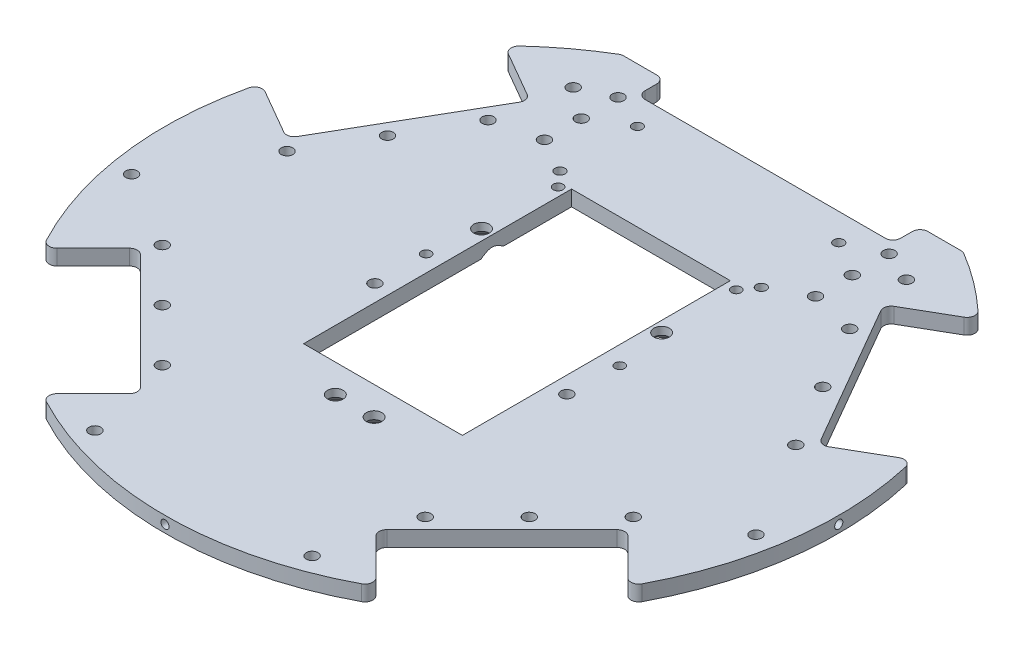
SolidWorks part; units mm, degrees
ref_plane "Front Plane" through (0, 0, 0) normal (0, 0, 1) x (1, 0, 0)
ref_plane "Top Plane" through (0, 0, 0) normal (0, 1, 0) x (1, 0, 0)
ref_plane "Right Plane" through (0, 0, 0) normal (1, 0, 0) x (0, 0, -1)
sketch "Sketch1" plane through (0, 0, 0) normal (0, 1, 0) x (1, 0, 0)
  line L0 (0, 75) -> (0, -70.0325) construction
  line L1 (0, 0) -> (57.1577, 33) construction
  line L2 (0, 0) -> (46.669, -46.669) construction
  line L3 (45.6577, 52.9186) -> (68.6577, 13.0814)
  line L4 (-44.0908, 75) -> (44.0908, 75) construction
  line L5 (62.9325, -30.4056) -> (30.4056, -62.9325)
  line L6 (45.6577, 52.9186) -> (61.1636, 61.8709)
  line L7 (68.6577, 13.0814) -> (84.1636, 22.0338)
  line L8 (30.4056, -62.9325) -> (43.0661, -75.593)
  line L9 (62.9325, -30.4056) -> (75.593, -43.0661)
  line L10 (-33, 69) -> (33, 69)
  line L11 (33, 69) -> (33, 75)
  line L12 (33, 75) -> (44.0908, 75)
  line L13 (0, 0) -> (-46.669, -46.669) construction
  line L14 (0, 0) -> (-57.1577, 33) construction
  line L15 (-33, 75) -> (-44.0908, 75)
  line L16 (-33, 69) -> (-33, 75)
  line L17 (-62.9325, -30.4056) -> (-75.593, -43.0661)
  line L18 (-30.4056, -62.9325) -> (-43.0661, -75.593)
  line L19 (-68.6577, 13.0814) -> (-84.1636, 22.0338)
  line L20 (-45.6577, 52.9186) -> (-61.1636, 61.8709)
  line L21 (-62.9325, -30.4056) -> (-30.4056, -62.9325)
  line L22 (-45.6577, 52.9186) -> (-68.6577, 13.0814)
  arc A0 (-43.0661, -75.593) -> (43.0661, -75.593) centre (0, 0) ccw
  arc A1 (61.1636, 61.8709) -> (44.0908, 75) centre (0, 0) ccw
  arc A2 (75.593, -43.0661) -> (84.1636, 22.0338) centre (0, 0) ccw
  arc A3 (-75.593, -43.0661) -> (-84.1636, 22.0338) centre (0, 0) cw
  arc A4 (-61.1636, 61.8709) -> (-44.0908, 75) centre (0, 0) cw
  point P27 (0, 69)
  dimension "D1" = 87
  dimension "D2" = 75
  dimension "D3" = 66
  dimension "D4" = 60
  dimension "D5" = 45
  dimension "D6" = 46
  dimension "D7" = 46
  dimension "D8" = 33
  dimension "D9" = 6
extrude "Boss-Extrude1" add sketch "Sketch1" along normal mid plane 4
fillet "Fillet1" radius 2 20 edges at (33, 0, -75) (-33, 0, -75) (44.0908, 0, -75) (68.6577, 0, -13.0814) (84.1636, 0, -22.0338) (45.6577, 0, -52.9186) (61.1636, 0, -61.8709) (62.9325, 0, 30.4056) (43.0661, 0, 75.593) (30.4056, 0, 62.9325) (75.593, 0, 43.0661) (-43.0661, 0, 75.593) (-30.4056, 0, 62.9325) (-75.593, 0, 43.0661) (-62.9325, 0, 30.4056) (-68.6577, 0, -13.0814) (-84.1636, 0, -22.0338) (-45.6577, 0, -52.9186) (-44.0908, 0, -75) (-61.1636, 0, -61.8709)
sketch "Sketch2" plane through (0, -2, 0) normal (0, -1, 0) x (-1, 0, 0)
  line L0 (46.6936, 43.1244) -> (65.6936, 10.2154) construction
  line L1 (60.8112, -26.8701) -> (33.9411, -53.7401) construction
  line L2 (46.6577, 51.1865) -> (67.6577, 14.8135) construction
  line L3 (61.5183, -31.8198) -> (31.8198, -61.5183) construction
  line L4 (70.3897, 14.0814) -> (81.8562, 20.7016) construction
  line L5 (73.7091, -41.1822) -> (64.3467, -31.8198) construction
  line L6 (35, 65) -> (35, 46) construction
  line L7 (26, 61) -> (26, 41) construction
  line L8 (35, 75) -> (43.5431, 75) construction
  line L9 (-33, 69) -> (33, 69) construction
  line L10 (-33, 69) -> (33, 69) construction
  line L11 (0, 69) -> (0, -87) construction
  line L12 (-26, 61) -> (-26, 41) construction
  line L13 (-35, 65) -> (-35, 46) construction
  line L14 (-60.8112, -26.8701) -> (-33.9411, -53.7401) construction
  line L15 (-46.6936, 43.1244) -> (-65.6936, 10.2154) construction
  arc A0 (-40.7037, -76.8909) -> (40.7037, -76.8909) centre (0, 0) ccw construction
  point P0 (46.6936, 43.1244)
  point P1 (56.1936, 26.6699)
  point P2 (65.6936, 10.2154)
  point P3 (60.8112, -26.8701)
  point P4 (47.3762, -40.3051)
  point P5 (33.9411, -53.7401)
  point P18 (35, 65)
  point P19 (35, 55.5)
  point P20 (35, 46)
  point P21 (26, 61)
  point P22 (26, 41)
  point P29 (0, 69)
  point P34 (0, 69)
  point P48 (-35, 55.5)
  point P49 (-47.3762, -40.3051)
  point P50 (-56.1936, 26.6699)
  dimension "D1" = 38
  dimension "D2" = 38
  dimension "D3" = 4
  dimension "D4" = 4
  dimension "D5" = 18
  dimension "D6" = 18
  dimension "D7" = 19
  dimension "D8" = 35
  dimension "10" = 10
  dimension "D9" = 20
  dimension "D10" = 8
  dimension "D11" = 26
hole_wizard "CSK for M3 SFHCS1" positions "3DSketch1" profile "Sketch3" countersink size "M3" standard "ANSI Metric"
sketch3d "3DSketch1"
  point P0 (46.6936, -2, -43.1244)
  point P3 (56.1936, -2, -26.6699)
  point P6 (65.6936, -2, -10.2154)
  point P9 (60.8112, -2, 26.8701)
  point P12 (47.3762, -2, 40.3051)
  point P15 (33.9411, -2, 53.7401)
  point P18 (-33.9411, -2, 53.7401)
  point P21 (-47.3762, -2, 40.3051)
  point P24 (-60.8112, -2, 26.8701)
  point P27 (-46.6936, -2, -43.1244)
  point P30 (-56.1936, -2, -26.6699)
  point P33 (-65.6936, -2, -10.2154)
  point P36 (-35, -2, -65)
  point P39 (-35, -2, -55.5)
  point P42 (-35, -2, -46)
  point P45 (35, -2, -46)
  point P48 (35, -2, -55.5)
  point P51 (35, -2, -65)
sketch "Sketch3" plane through (46.6936, -2, -43.1244) normal (1, 0, 0) x (0, 0, -1)
  line L0 (0, 0) -> (0, 10.4013)
  line L1 (0, 10.4013) -> (1.5, 9.5)
  line L2 (1.5, 9.5) -> (1.5, 1.3)
  line L3 (1.5, 1.3) -> (2.8, 0)
  line L5 (2.8, 0) -> (0, 0)
  line L6 (-1.5, 1.3) -> (-2.8, 0) construction
  line L10 (0, 10.4013) -> (-1.5, 9.5) construction
  line L11 (0, -6.35) -> (0, 107.95) construction
  dimension "Hole Dia." = 3
  dimension "Hole Depth" = 9.5
  dimension "Near C'Sink Dia." = 5.6
  dimension "Near C'Sink Angle" = 90
  dimension "Drill Angle" = 118
sketch "Sketch4" plane through (0, -2, 0) normal (0, -1, 0) x (1, 0, 0)
  line L0 (0, 0) -> (-43.0182, -61.4364) construction
  line L1 (0, 0) -> (-28.0457, 77.0548) construction
  line L2 (0, -69) -> (0, 87) construction
  line L3 (0, 0) -> (-80.6164, 15) construction
  line L4 (0, -69) -> (0, 87) construction
  line L5 (0, 0) -> (80.6164, 15) construction
  line L6 (0, 0) -> (28.0457, 77.0548) construction
  line L7 (0, 0) -> (43.0182, -61.4364) construction
  dimension "D1" = 75
  dimension "D2" = 35
  dimension "D3" = 82
  dimension "D4" = 20
  dimension "D5" = 82
  dimension "D6" = 15
hole_wizard "CSK for M3 SFHCS2" positions "3DSketch2" profile "Sketch5" countersink size "M3" standard "ANSI Metric"
sketch3d "3DSketch2"
  point P0 (43.0182, -2, -61.4364)
  point P3 (80.6164, -2, 15)
  point P6 (28.0457, -2, 77.0548)
  point P9 (-28.0457, -2, 77.0548)
  point P12 (-80.6164, -2, 15)
  point P15 (-43.0182, -2, -61.4364)
sketch "Sketch5" plane through (43.0182, -2, -61.4364) normal (1, 0, 0) x (0, 0, -1)
  line L0 (0, 0) -> (0, 10.4013)
  line L1 (0, 10.4013) -> (1.5, 9.5)
  line L2 (1.5, 9.5) -> (1.5, 1.3)
  line L3 (1.5, 1.3) -> (2.8, 0)
  line L5 (2.8, 0) -> (0, 0)
  line L6 (-1.5, 1.3) -> (-2.8, 0) construction
  line L10 (0, 10.4013) -> (-1.5, 9.5) construction
  line L11 (0, -6.35) -> (0, 107.95) construction
  dimension "Hole Dia." = 3
  dimension "Hole Depth" = 9.5
  dimension "Near C'Sink Dia." = 5.6
  dimension "Near C'Sink Angle" = 90
  dimension "Drill Angle" = 118
hole_wizard "CSK for M3 SFHCS3" positions "3DSketch3" profile "Sketch6" countersink size "M3" standard "ANSI Metric"
sketch3d "3DSketch3"
  point P0 (26, -2, -41)
  point P3 (26, -2, -61)
  point P6 (-26, -2, -41)
  point P9 (-26, -2, -61)
sketch "Sketch6" plane through (26, -2, -41) normal (1, 0, 0) x (0, 0, -1)
  line L0 (0, 0) -> (0, 10.2811)
  line L1 (0, 10.2811) -> (1.3, 9.5)
  line L2 (1.3, 9.5) -> (1.3, 1)
  line L3 (1.3, 1) -> (2.3, 0)
  line L5 (2.3, 0) -> (0, 0)
  line L6 (-1.3, 1) -> (-2.3, 0) construction
  line L10 (0, 10.2811) -> (-1.3, 9.5) construction
  line L11 (0, -6.35) -> (0, 107.95) construction
  dimension "Hole Dia." = 2.6
  dimension "Hole Depth" = 9.5
  dimension "Near C'Sink Dia." = 4.6
  dimension "Near C'Sink Angle" = 90
  dimension "Drill Angle" = 118
sketch "Sketch7" plane through (0, 0, 0) normal (0, 1, 0) x (1, 0, 0)
  arc A0 (-84.8058, 19.4159) -> (-76.8909, -40.7037) centre (0, 0) ccw construction
  arc A1 (76.8909, -40.7037) -> (84.8058, 19.4159) centre (0, 0) ccw construction
  arc A2 (-40.7037, -76.8909) -> (40.7037, -76.8909) centre (0, 0) ccw construction
  arc A3 (59.2176, 63.736) -> (44.5676, 74.7176) centre (0, 0) ccw construction
  arc A4 (-44.5676, 74.7176) -> (-59.2176, 63.736) centre (0, 0) ccw construction
  point P0 (-86.2557, -11.3558)
  point P1 (86.2557, -11.3558)
  point P5 (0, -87)
  point P9 (52.1823, 69.6133)
  point P13 (-52.1823, 69.6133)
ref_plane "Plane1" through (87, 0, 0) normal (1, 0, 0) x (0, 0, -1)
sketch "Sketch9" plane through (87, 0, 0) normal (1, 0, 0) x (0, 0, -1)
  circle A0 centre (0, 0) radius 1.05
  dimension "D1" = 2.1
ref_plane "Plane2" through (0, 0, 87) normal (0, 0, 1) x (1, 0, 0)
sketch "Sketch10" plane through (0, 0, 87) normal (0, 0, 1) x (1, 0, 0)
  circle A0 centre (0, 0) radius 1.05
  dimension "D1" = 2.1
ref_plane "Plane3" through (52.1823, 0, -69.6133) normal (0.5998, 0, -0.8002) x (-0.8002, 0, -0.5998)
sketch "Sketch11" plane through (52.1823, 0, -69.6133) normal (0.5998, 0, -0.8002) x (-0.8002, 0, -0.5998)
  circle A0 centre (0, 0) radius 1.05
  dimension "D1" = 2.1
sketch "Sketch12" plane through (0, 2, 0) normal (0, 1, 0) x (1, 0, 0)
  line L0 (-23.25, 18) -> (23.25, 18) construction
  line L1 (24.78, -8) -> (-24.78, -8) construction
  line L2 (-5, -38) -> (5, -38) construction
  line L3 (33, 69) -> (-33, 69) construction
  line L4 (-35, 75) -> (-43.5431, 75) construction
  point P0 (-23.25, 18)
  point P1 (23.25, 18)
  point P2 (-5, -38)
  point P3 (5, -38)
  point P4 (-24.78, -8)
  point P5 (24.78, -8)
  point P14 (0, 18)
  point P16 (0, -8)
  point P17 (0, -38)
  dimension "D1" = 51
  dimension "D2" = 83
  dimension "D3" = 56
  dimension "D4" = 49.56
  dimension "D5" = 10
  dimension "D6" = 46.5
sketch "Sketch14" plane through (0, -2, 0) normal (0, -1, 0) x (1, 0, 0)
  point P0 (23.25, -18)
  point P1 (-23.25, -18)
  point P3 (-24.78, 8)
  point P5 (24.78, 8)
  point P7 (5, 38)
  point P9 (-5, 38)
hole_wizard "CSK for M4 SFHCS3" positions "3DSketch7" profile "Sketch16" countersink size "M4" standard "ANSI Metric"
sketch3d "3DSketch7"
  point P0 (23.25, -2, -18)
  point P3 (-23.25, -2, -18)
  point P6 (-5, -2, 38)
  point P9 (5, -2, 38)
sketch "Sketch16" plane through (23.25, -2, -18) normal (1, 0, 0) x (0, 0, -1)
  line L0 (0, 0) -> (0, 10.7017)
  line L1 (0, 10.7017) -> (2, 9.5)
  line L2 (2, 9.5) -> (2, 2)
  line L3 (2, 2) -> (4, 0)
  line L5 (4, 0) -> (0, 0)
  line L6 (-2, 2) -> (-4, 0) construction
  line L10 (0, 10.7017) -> (-2, 9.5) construction
  line L11 (0, -6.35) -> (0, 107.95) construction
  dimension "Hole Dia." = 4
  dimension "Hole Depth" = 9.5
  dimension "Near C'Sink Dia." = 8
  dimension "Near C'Sink Angle" = 90
  dimension "Drill Angle" = 118
hole_wizard "CSK for M3 SFHCS4" positions "3DSketch8" profile "Sketch17" countersink size "M3" standard "ANSI Metric"
sketch3d "3DSketch8"
  point P0 (24.78, -2, 8)
  point P3 (-24.78, -2, 8)
  point P6 (22, -2, 8)
sketch "Sketch17" plane through (24.78, -2, 8) normal (1, 0, 0) x (0, 0, -1)
  line L0 (0, 0) -> (0, 10.4013)
  line L1 (0, 10.4013) -> (1.5, 9.5)
  line L2 (1.5, 9.5) -> (1.5, 1.3)
  line L3 (1.5, 1.3) -> (2.8, 0)
  line L5 (2.8, 0) -> (0, 0)
  line L6 (-1.5, 1.3) -> (-2.8, 0) construction
  line L10 (0, 10.4013) -> (-1.5, 9.5) construction
  line L11 (0, -6.35) -> (0, 107.95) construction
  dimension "Hole Dia." = 3
  dimension "Hole Depth" = 9.5
  dimension "Near C'Sink Dia." = 5.6
  dimension "Near C'Sink Angle" = 90
  dimension "Drill Angle" = 118
extrude "Cut-Extrude1" cut sketch "Sketch9" against normal blind 8
extrude "Cut-Extrude2" cut sketch "Sketch10" against normal blind 8
extrude "Cut-Extrude3" cut sketch "Sketch11" against normal blind 8
mirror "Mirror1" about plane through (0, 0, 0) normal (1, 0, 0) of "Cut-Extrude3", "Cut-Extrude2", "Cut-Extrude1"
sketch "Sketch18" plane through (0, 2, 0) normal (0, 1, 0) x (1, 0, 0)
  line L0 (-44.8999, 78) -> (44.8999, 78) construction
  line L1 (-35, 75) -> (-43.5431, 75) construction
  circle A0 centre (0, 0) radius 90 construction
  dimension "D1" = 180
  dimension "D2" = 3
hole_wizard "M2.5x0.45 Tapped Hole1" positions "3DSketch9" profile "Sketch19" tap size "M2.5x0.45" standard "ANSI Metric"
sketch3d "3DSketch9"
  line L0 (-35, 2, -75) -> (-43.5431, 2, -75) construction
  line L1 (43.5431, 2, -75) -> (35, 2, -75) construction
  line L2 (-35, -2, -75) -> (-43.5431, -2, -75) construction
  point P0 (-39.2715, 0, -75)
  point P2 (39.4456, 0, -75)
  point P11 (-39.2715, -2, -75)
  dimension "D1" = 2
  dimension "D2" = 2
sketch "Sketch19" plane through (-39.2715, 0, -75) normal (1, 0, 0) x (0, 1, 0)
  line L0 (0, 0) -> (0, 6.9659)
  line L1 (0, 6.9659) -> (1.025, 6.35)
  line L2 (1.025, 6.35) -> (1.025, 0)
  line L5 (1.025, 0) -> (0, 0)
  line L10 (0, 6.9659) -> (-1.025, 6.35) construction
  line L11 (0, -6.35) -> (0, 107.95) construction
  dimension "Tap Drill Dia." = 2.05
  dimension "Tap Drill Depth" = 6.35
  dimension "Drill Angle" = 118
sketch "Sketch21" plane through (0, 2, 0) normal (0, 1, 0) x (1, 0, 0)
  line L17 (43.5431, 75) -> (35, 75)
  line L18 (33, 73) -> (33, 69)
  line L19 (33, 69) -> (-33, 69)
  line L20 (-33, 69) -> (-33, 73)
  line L21 (-35, 75) -> (-43.5431, 75)
  line L22 (-58.8562, 60.5388) -> (-47.3897, 53.9186)
  line L23 (-46.6577, 51.1865) -> (-67.6577, 14.8135)
  line L24 (-70.3897, 14.0814) -> (-81.8562, 20.7016)
  line L25 (-73.7091, -41.1822) -> (-64.3467, -31.8198)
  line L26 (-61.5183, -31.8198) -> (-31.8198, -61.5183)
  line L27 (-31.8198, -64.3467) -> (-41.1822, -73.7091)
  line L28 (41.1822, -73.7091) -> (31.8198, -64.3467)
  line L29 (31.8198, -61.5183) -> (61.5183, -31.8198)
  line L30 (64.3467, -31.8198) -> (73.7091, -41.1822)
  line L31 (81.8562, 20.7016) -> (70.3897, 14.0814)
  line L32 (67.6577, 14.8135) -> (46.6577, 51.1865)
  line L33 (47.3897, 53.9186) -> (58.8562, 60.5388)
  line L34 (43.5431, 75) -> (35, 75)
  line L35 (33, 73) -> (33, 69)
  line L36 (33, 69) -> (-33, 69)
  line L37 (-33, 69) -> (-33, 73)
  line L38 (-35, 75) -> (-43.5431, 75)
  line L39 (-58.8562, 60.5388) -> (-47.3897, 53.9186)
  line L40 (-46.6577, 51.1865) -> (-67.6577, 14.8135)
  line L41 (-70.3897, 14.0814) -> (-81.8562, 20.7016)
  line L42 (-73.7091, -41.1822) -> (-64.3467, -31.8198)
  line L43 (-61.5183, -31.8198) -> (-31.8198, -61.5183)
  line L44 (-31.8198, -64.3467) -> (-41.1822, -73.7091)
  line L45 (41.1822, -73.7091) -> (31.8198, -64.3467)
  line L46 (31.8198, -61.5183) -> (61.5183, -31.8198)
  line L47 (64.3467, -31.8198) -> (73.7091, -41.1822)
  line L48 (81.8562, 20.7016) -> (70.3897, 14.0814)
  line L49 (67.6577, 14.8135) -> (46.6577, 51.1865)
  line L50 (47.3897, 53.9186) -> (58.8562, 60.5388)
  circle A1 centre (25.24, 5.2127) radius 1.25
  circle A2 centre (25.24, 5.2127) radius 1.25
  circle A3 centre (-24.76, 5.2127) radius 1.25
  circle A4 centre (-24.76, 5.2127) radius 1.25
  circle A5 centre (-22.685, 37.2127) radius 1.25
  circle A6 centre (-22.685, 37.2127) radius 1.25
  circle A7 centre (23.315, 37.2127) radius 1.25
  circle A8 centre (23.315, 37.2127) radius 1.25
  arc A27 (35, 75) -> (33, 73) centre (35, 73) ccw
  arc A30 (-33, 73) -> (-35, 75) centre (-35, 73) ccw
  arc A31 (-43.5431, 75) -> (-44.5676, 74.7176) centre (-43.5431, 73) ccw
  arc A32 (-44.5676, 74.7176) -> (-59.2176, 63.736) centre (0, 0) ccw
  arc A33 (-59.2176, 63.736) -> (-58.8562, 60.5388) centre (-57.8562, 62.2708) ccw
  arc A34 (-46.6577, 51.1865) -> (-47.3897, 53.9186) centre (-48.3897, 52.1865) ccw
  arc A35 (-70.3897, 14.0814) -> (-67.6577, 14.8135) centre (-69.3897, 15.8135) ccw
  arc A36 (-81.8562, 20.7016) -> (-84.8058, 19.4159) centre (-82.8562, 18.9696) ccw
  arc A37 (-84.8058, 19.4159) -> (-76.8909, -40.7037) centre (0, 0) ccw
  arc A38 (-76.8909, -40.7037) -> (-73.7091, -41.1822) centre (-75.1233, -39.768) ccw
  arc A39 (-61.5183, -31.8198) -> (-64.3467, -31.8198) centre (-62.9325, -33.234) ccw
  arc A40 (-31.8198, -64.3467) -> (-31.8198, -61.5183) centre (-33.234, -62.9325) ccw
  arc A41 (-41.1822, -73.7091) -> (-40.7037, -76.8909) centre (-39.768, -75.1233) ccw
  arc A42 (-40.7037, -76.8909) -> (40.7037, -76.8909) centre (0, 0) ccw
  arc A43 (40.7037, -76.8909) -> (41.1822, -73.7091) centre (39.768, -75.1233) ccw
  arc A44 (31.8198, -61.5183) -> (31.8198, -64.3467) centre (33.234, -62.9325) ccw
  arc A45 (64.3467, -31.8198) -> (61.5183, -31.8198) centre (62.9325, -33.234) ccw
  arc A46 (73.7091, -41.1822) -> (76.8909, -40.7037) centre (75.1233, -39.768) ccw
  arc A47 (76.8909, -40.7037) -> (84.8058, 19.4159) centre (0, 0) ccw
  arc A48 (84.8058, 19.4159) -> (81.8562, 20.7016) centre (82.8562, 18.9696) ccw
  arc A49 (67.6577, 14.8135) -> (70.3897, 14.0814) centre (69.3897, 15.8135) ccw
  arc A50 (47.3897, 53.9186) -> (46.6577, 51.1865) centre (48.3897, 52.1865) ccw
  arc A51 (58.8562, 60.5388) -> (59.2176, 63.736) centre (57.8562, 62.2708) ccw
  arc A52 (59.2176, 63.736) -> (44.5676, 74.7176) centre (0, 0) ccw
  arc A53 (44.5676, 74.7176) -> (43.5431, 75) centre (43.5431, 73) ccw
  arc A54 (35, 75) -> (33, 73) centre (35, 73) ccw
  arc A57 (-33, 73) -> (-35, 75) centre (-35, 73) ccw
  arc A58 (-43.5431, 75) -> (-44.5676, 74.7176) centre (-43.5431, 73) ccw
  arc A59 (-44.5676, 74.7176) -> (-59.2176, 63.736) centre (0, 0) ccw
  arc A60 (-59.2176, 63.736) -> (-58.8562, 60.5388) centre (-57.8562, 62.2708) ccw
  arc A61 (-46.6577, 51.1865) -> (-47.3897, 53.9186) centre (-48.3897, 52.1865) ccw
  arc A62 (-70.3897, 14.0814) -> (-67.6577, 14.8135) centre (-69.3897, 15.8135) ccw
  arc A63 (-81.8562, 20.7016) -> (-84.8058, 19.4159) centre (-82.8562, 18.9696) ccw
  arc A64 (-84.8058, 19.4159) -> (-76.8909, -40.7037) centre (0, 0) ccw
  arc A65 (-76.8909, -40.7037) -> (-73.7091, -41.1822) centre (-75.1233, -39.768) ccw
  arc A66 (-61.5183, -31.8198) -> (-64.3467, -31.8198) centre (-62.9325, -33.234) ccw
  arc A67 (-31.8198, -64.3467) -> (-31.8198, -61.5183) centre (-33.234, -62.9325) ccw
  arc A68 (-41.1822, -73.7091) -> (-40.7037, -76.8909) centre (-39.768, -75.1233) ccw
  arc A69 (-40.7037, -76.8909) -> (40.7037, -76.8909) centre (0, 0) ccw
  arc A70 (40.7037, -76.8909) -> (41.1822, -73.7091) centre (39.768, -75.1233) ccw
  arc A71 (31.8198, -61.5183) -> (31.8198, -64.3467) centre (33.234, -62.9325) ccw
  arc A72 (64.3467, -31.8198) -> (61.5183, -31.8198) centre (62.9325, -33.234) ccw
  arc A73 (73.7091, -41.1822) -> (76.8909, -40.7037) centre (75.1233, -39.768) ccw
  arc A74 (76.8909, -40.7037) -> (84.8058, 19.4159) centre (0, 0) ccw
  arc A75 (84.8058, 19.4159) -> (81.8562, 20.7016) centre (82.8562, 18.9696) ccw
  arc A76 (67.6577, 14.8135) -> (70.3897, 14.0814) centre (69.3897, 15.8135) ccw
  arc A77 (47.3897, 53.9186) -> (46.6577, 51.1865) centre (48.3897, 52.1865) ccw
  arc A78 (58.8562, 60.5388) -> (59.2176, 63.736) centre (57.8562, 62.2708) ccw
  arc A79 (59.2176, 63.736) -> (44.5676, 74.7176) centre (0, 0) ccw
  arc A80 (44.5676, 74.7176) -> (43.5431, 75) centre (43.5431, 73) ccw
  dimension "D1" = 0
  dimension "D2" = 0
  dimension "D3" = 0
  dimension "D4" = 0
  dimension "D5" = 0
extrude "Cut-Extrude4" cut sketch "Sketch21" against normal up to next contours A2 | A8 | A4 | A6
sketch "Sketch23" plane through (0, 0, -69) normal (0, 0, -1) x (-1, 0, 0)
  line L1 (33, -2) -> (-33, -2)
  line L2 (33, -2) -> (33, 2)
  line L3 (33, 2) -> (-33, 2)
  line L4 (-33, -2) -> (-33, 2)
extrude "Cut-Extrude6" cut sketch "Sketch23" against normal blind 1
fillet "Fillet2" radius 2 2 edges at (33, 0, -68) (-33, 0, -68)
sketch "Sketch24" plane through (0, -2, 0) normal (0, -1, 0) x (1, 0, 0)
  line L0 (31, -68) -> (-31, -68) construction
  line L1 (-20.5, 30.7) -> (20.5, 30.7)
  line L2 (-20.5, 30.7) -> (-20.5, -38.5)
  line L3 (-20.5, -38.5) -> (20.5, -38.5)
  line L4 (20.5, 30.7) -> (20.5, -38.5)
  point P6 (0, -68)
  point P7 (0, 30.7)
  dimension "D1" = 29.5
  dimension "D2" = 41
  dimension "D3" = 69.2
extrude "Cut-Extrude9" cut sketch "Sketch24" against normal blind 10 contours L2 L3 L4 L1
